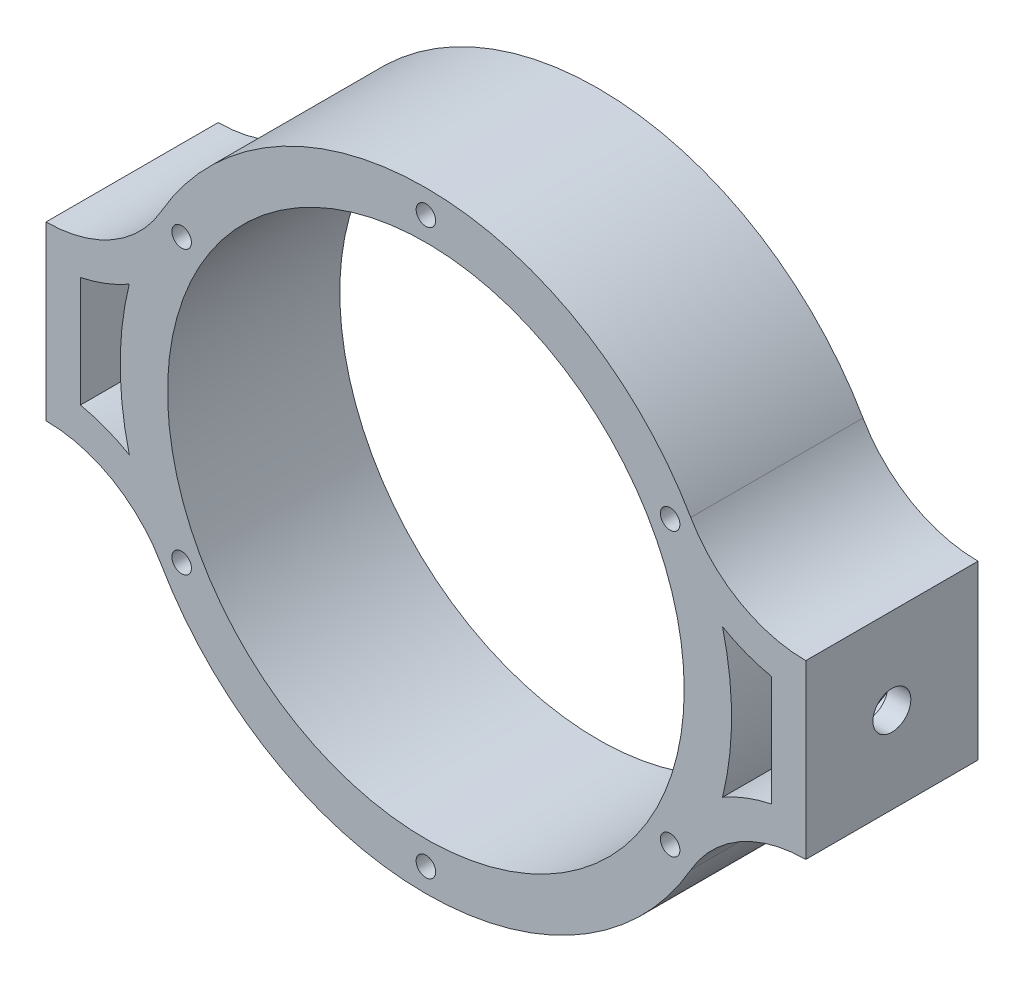
SolidWorks part; units mm, degrees
material "6061-T6 (SS)"
ref_plane "Front Plane" through (0, 0, 0) normal (0, 0, 1) x (1, 0, 0)
ref_plane "Top Plane" through (0, 0, 0) normal (0, 1, 0) x (1, 0, 0)
ref_plane "Right Plane" through (0, 0, 0) normal (1, 0, 0) x (0, 0, -1)
sketch "Sketch1" plane through (0, 0, 0) normal (0, 0, 1) x (1, 0, 0)
  line L0 (-66.175, 0) -> (66.175, 0) construction
  line L1 (-66.175, -15) -> (-66.175, 15)
  line L2 (-66.175, 15) -> (-51.0937, 15) construction
  line L3 (0, 0) -> (0, 53.25) construction
  line L4 (66.175, -15) -> (66.175, 15)
  circle A0 centre (0, 0) radius 53.25 construction
  arc A1 (-66.175, 15) -> (-46.1423, 26.5792) centre (-66.175, 38.1185) ccw
  arc A4 (66.175, 15) -> (46.1423, 26.5792) centre (66.175, 38.1185) cw
  arc A5 (-46.1423, 26.5792) -> (46.1423, 26.5792) centre (0, 0) cw
  circle A7 centre (0, 0) radius 45
  arc A11 (66.175, -15) -> (46.1423, -26.5792) centre (66.175, -38.1185) ccw
  arc A12 (-46.1423, -26.5792) -> (46.1423, -26.5792) centre (0, 0) ccw
  arc A13 (-66.175, -15) -> (-46.1423, -26.5792) centre (-66.175, -38.1185) cw
  point P5 (0, 0)
  point P8 (-66.175, 0)
  dimension "D1" = 53.25
  dimension "D2" = 132.35
  dimension "D3" = 90
  dimension "D4" = 30
extrude "Boss-Extrude1" add sketch "Sketch1" along normal mid plane 30
sketch "Sketch2" plane through (0, 0, 15) normal (0, 0, 1) x (1, 0, 0)
  line L2 (0, 0) -> (0, -53.25) construction
  line L3 (-60.175, -9.6249) -> (-60.175, 9.6249)
  line L4 (-60.175, -9.6249) -> (-60.175, 9.6249)
  line L5 (60.175, -9.6249) -> (60.175, 9.6249)
  arc A0 (46.1423, 26.5792) -> (-46.1423, 26.5792) centre (0, 0) ccw construction
  arc A1 (46.1423, 26.5792) -> (-46.1423, 26.5792) centre (0, 0) ccw construction
  circle A2 centre (0, 0) radius 53.25 construction
  arc A7 (-51.6716, 12.869) -> (-51.6716, -12.869) centre (0, 0) ccw
  arc A8 (51.6716, 12.869) -> (51.6716, -12.869) centre (0, 0) cw
  arc A9 (-40.9432, -23.5843) -> (-60.175, -9.6249) centre (-66.175, -38.1185) ccw
  arc A10 (-60.175, 9.6249) -> (-40.9432, 23.5843) centre (-66.175, 38.1185) ccw
  arc A11 (-51.6716, -12.869) -> (-60.175, -9.6249) centre (-66.175, -38.1185) ccw
  arc A12 (-60.175, 9.6249) -> (-51.6716, 12.869) centre (-66.175, 38.1185) ccw
  arc A13 (60.175, 9.6249) -> (51.6716, 12.869) centre (66.175, 38.1185) cw
  arc A14 (51.6716, -12.869) -> (60.175, -9.6249) centre (66.175, -38.1185) cw
  dimension "D1" = 6
extrude "Cut-Extrude1" cut sketch "Sketch2" against normal through all both and the other way through all
sketch "Sketch3" plane through (-66.175, 0, 0) normal (-1, 0, 0) x (0, 0, 1)
  point P0 (0, 0)
hole_wizard "M6 Clearance Hole1" positions "Sketch3" profile "Sketch4" hole size "M6" standard "ANSI Metric"
sketch "Sketch4" plane through (-66.175, 0, 0) normal (0, 1, 0) x (0, 0, 1)
  line L0 (0, 0) -> (0, 7.9828)
  line L1 (0, 7.9828) -> (3.3, 6)
  line L2 (3.3, 6) -> (3.3, 0)
  line L5 (3.3, 0) -> (0, 0)
  line L10 (0, 7.9828) -> (-3.3, 6) construction
  line L11 (0, -6.35) -> (0, 107.95) construction
  dimension "Hole Dia." = 6.6
  dimension "Hole Depth" = 6
  dimension "Drill Angle" = 118
sketch "Sketch5" plane through (66.175, 0, 0) normal (1, 0, 0) x (0, 0, -1)
  point P0 (0, 0)
hole_wizard "M6 Clearance Hole2" positions "Sketch5" profile "Sketch6" hole size "M6" standard "ANSI Metric"
sketch "Sketch6" plane through (66.175, 0, 0) normal (0, 1, 0) x (0, 0, -1)
  line L0 (0, 0) -> (0, 7.9828)
  line L1 (0, 7.9828) -> (3.3, 6)
  line L2 (3.3, 6) -> (3.3, 0)
  line L5 (3.3, 0) -> (0, 0)
  line L10 (0, 7.9828) -> (-3.3, 6) construction
  line L11 (0, -6.35) -> (0, 107.95) construction
  dimension "Hole Dia." = 6.6
  dimension "Hole Depth" = 6
  dimension "Drill Angle" = 118
sketch "Sketch7" plane through (0, 0, 15) normal (0, 0, 1) x (1, 0, 0)
  line L0 (0, 53.25) -> (0, 45) construction
  circle A0 centre (0, 0) radius 49.125 construction
  arc A2 (46.1423, 26.5792) -> (-46.1423, 26.5792) centre (0, 0) ccw construction
  circle A3 centre (0, 0) radius 45 construction
  point P10 (0, 49.125)
  point P26 (0, 49.125)
hole_wizard "M3 Clearance Hole1" positions "Sketch7" profile "Sketch8" hole size "M3" standard "ANSI Metric" end condition through all
sketch "Sketch8" plane through (0, 49.125, 15) normal (1, 0, 0) x (0, -1, 0)
  line L0 (0, 0) -> (0, 30)
  line L1 (0, 30) -> (1.7, 30)
  line L2 (1.7, 30) -> (1.7, 0)
  line L5 (1.7, 0) -> (0, 0)
  line L11 (0, -6.35) -> (0, 107.95) construction
  dimension "Thru Hole Dia." = 3.4
  dimension "Thru Hole Depth" = 30
pattern_circular "CirPattern1" count 6 over 360 about axis through (0, 0, 0) along (0, 0, 1) of "M3 Clearance Hole1"
sketch "Sketch9" plane through (-60.175, 0, 0) normal (1, 0, 0) x (0, 0, -1)
  line L1 (0, 5.889) -> (-5.1, 2.9445)
  line L2 (-5.1, 2.9445) -> (-5.1, -2.9445)
  line L3 (-5.1, -2.9445) -> (0, -5.889)
  line L4 (0, -5.889) -> (5.1, -2.9445)
  line L5 (5.1, -2.9445) -> (5.1, 2.9445)
  line L6 (5.1, 2.9445) -> (0, 5.889)
  circle A0 centre (0, 0) radius 3.3 construction
  circle A1 centre (0, 0) radius 3.3 construction
  circle A2 centre (0, 0) radius 5.1 construction
  dimension "D1" = 10.2
extrude "Cut-Extrude2" cut sketch "Sketch9" against normal blind 2
mirror "Mirror1" about plane through (0, 0, 0) normal (1, 0, 0) of "Cut-Extrude2"
